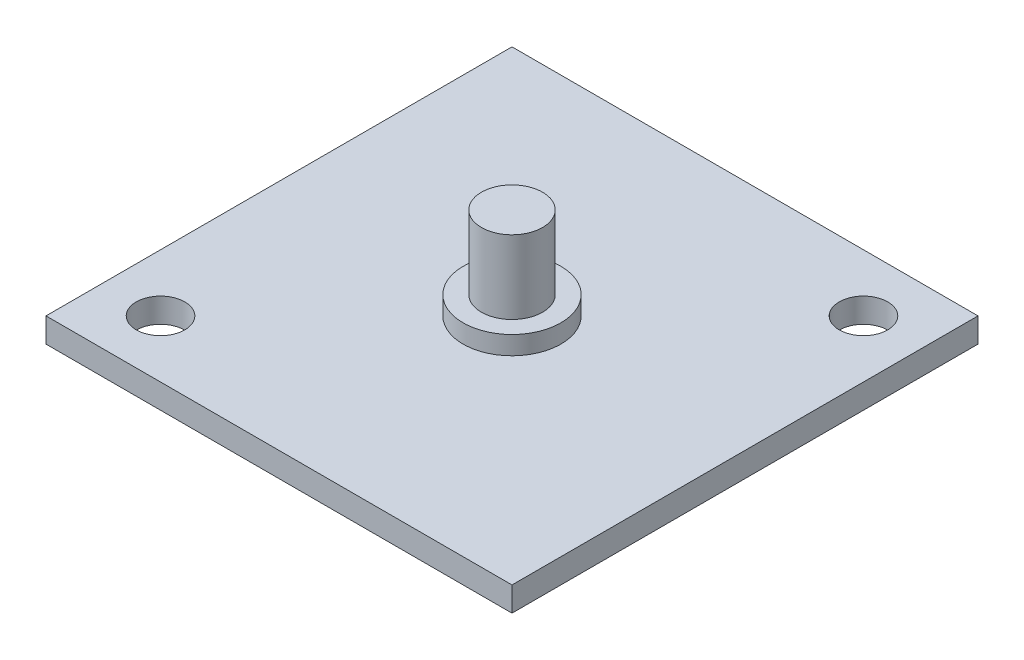
SolidWorks part; units mm, degrees
material "ABS"
ref_plane "Front Plane" through (0, 0, 0) normal (0, 0, 1) x (1, 0, 0)
ref_plane "Top Plane" through (0, 0, 0) normal (0, 1, 0) x (1, 0, 0)
ref_plane "Right Plane" through (0, 0, 0) normal (1, 0, 0) x (0, 0, -1)
sketch "Sketch1" plane through (0, 0, 0) normal (0, 1, 0) x (1, 0, 0)
  line L1 (-19.05, -19.05) -> (19.05, -19.05)
  line L2 (-19.05, -19.05) -> (-19.05, 19.05)
  line L3 (-19.05, 19.05) -> (19.05, 19.05)
  line L4 (19.05, -19.05) -> (19.05, 19.05)
  line L5 (-19.05, -19.05) -> (19.05, 19.05) construction
  line L6 (-19.05, 19.05) -> (19.05, -19.05) construction
  circle A0 centre (14.3684, 14.3684) radius 1.9844
  circle A1 centre (-14.3684, -14.3684) radius 1.9844
  point P0 (0, 0)
  dimension "D3" = 3.9688
  dimension "D1" = 38.1
  dimension "D2" = 38.1
extrude "Boss-Extrude1" add sketch "Sketch1" along normal blind 2
sketch "Sketch2" plane through (0, 2, 0) normal (0, 1, 0) x (1, 0, 0)
  line L0 (-19.05, 19.05) -> (19.05, -19.05) construction
  circle A0 centre (0, 0) radius 4.0005
  dimension "D1" = 8.001
extrude "Boss-Extrude2" add sketch "Sketch2" along normal blind 1.508
sketch "Sketch3" plane through (0, 3.508, 0) normal (0, 1, 0) x (1, 0, 0)
  circle A0 centre (0, 0) radius 2.5
  dimension "D1" = 5
extrude "Boss-Extrude3" add sketch "Sketch3" along normal blind 6
